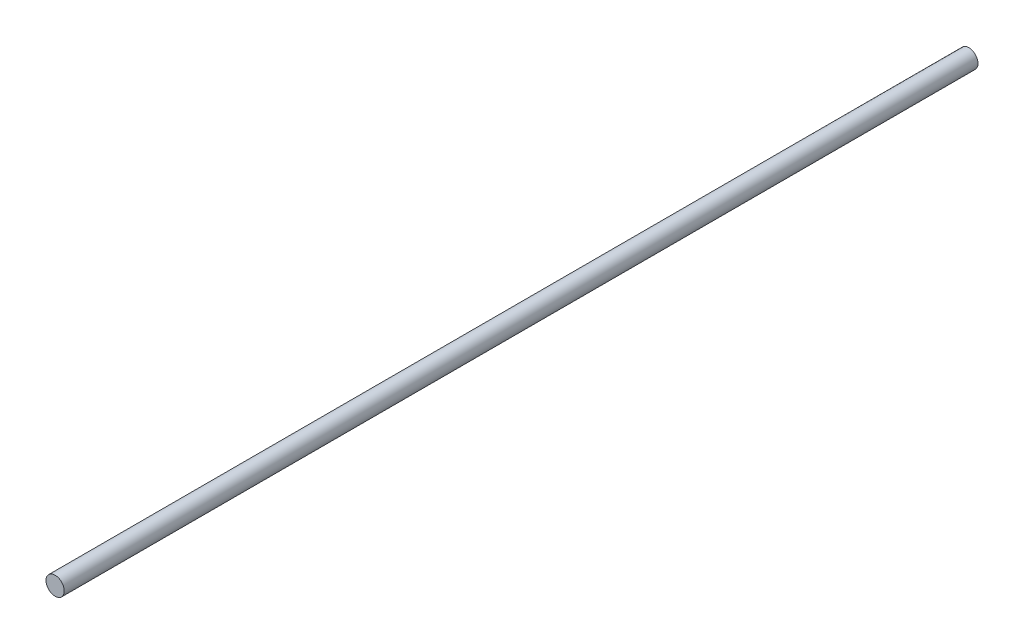
SolidWorks part; units mm, degrees
material "AISI 1045 Acier étiré à froid"
ref_plane "Plan de face" through (0, 0, 0) normal (0, 0, 1) x (1, 0, 0)
ref_plane "Plan de dessus" through (0, 0, 0) normal (0, 1, 0) x (1, 0, 0)
ref_plane "Plan de droite" through (0, 0, 0) normal (1, 0, 0) x (0, 0, -1)
sketch "Esquisse1" plane through (0, 0, 0) normal (0, 0, 1) x (1, 0, 0)
  circle A0 centre (0, 0) radius 2.5
  dimension "D1" = 5
extrude "Boss.-Extru.1" add sketch "Esquisse1" along normal blind 250
